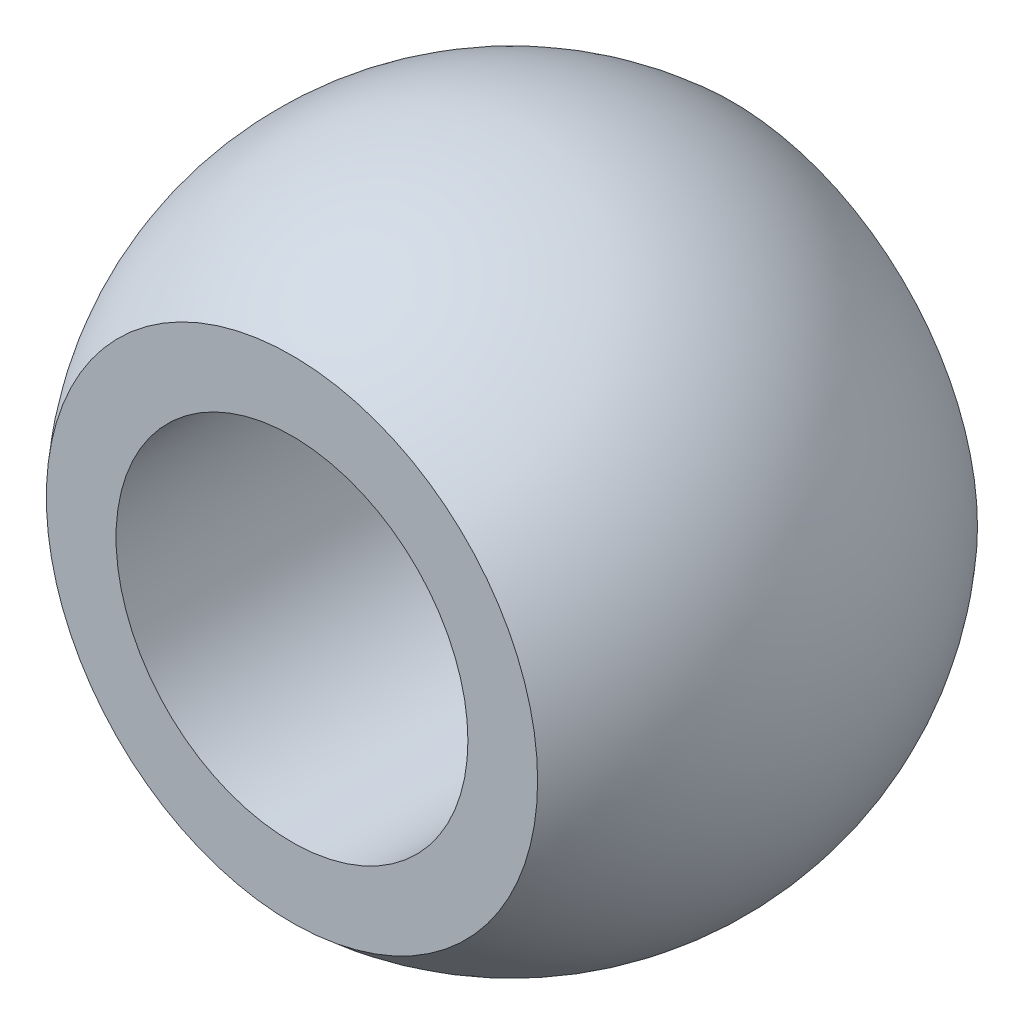
SolidWorks part; units mm, degrees
material "Alloy Steel"
ref_plane "Front Plane" through (0, 0, 0) normal (0, 0, 1) x (1, 0, 0)
ref_plane "Top Plane" through (0, 0, 0) normal (0, 1, 0) x (1, 0, 0)
ref_plane "Right Plane" through (0, 0, 0) normal (1, 0, 0) x (0, 0, -1)
sketch "Sketch1" plane through (0, 0, 0) normal (0, 0, 1) x (1, 0, 0)
  line L0 (0, -11.8999) -> (0, 11.8999) construction
  line L1 (0, 11.8999) -> (0, -11.8999)
  arc A0 (0, 11.8999) -> (0, -11.8999) centre (0, 0) cw
  dimension "D1" = 11.8999
revolve "Revolve1" add sketch "Sketch1" angle 360 about L0
sketch "Sketch2" plane through (0, 0, 0) normal (0, 0, 1) x (1, 0, 0)
  circle A0 centre (0, 0) radius 6.35
  dimension "D1" = 12.7
extrude "Extrude1" cut sketch "Sketch2" against normal mid plane 50.8
ref_plane "Plane1" through (0, 0, 7.9375) normal (0, 0, 1) x (1, 0, 0)
sketch "Sketch3" plane through (0, 0, 7.9375) normal (0, 0, 1) x (1, 0, 0)
  circle A0 centre (0, 0) radius 11.8999 construction
  circle A1 centre (0, 0) radius 11.8999
extrude "Extrude2" cut sketch "Sketch3" along normal up to next
mirror "Mirror1" about plane through (0, 0, 0) normal (0, 0, 1) of "Extrude2"
